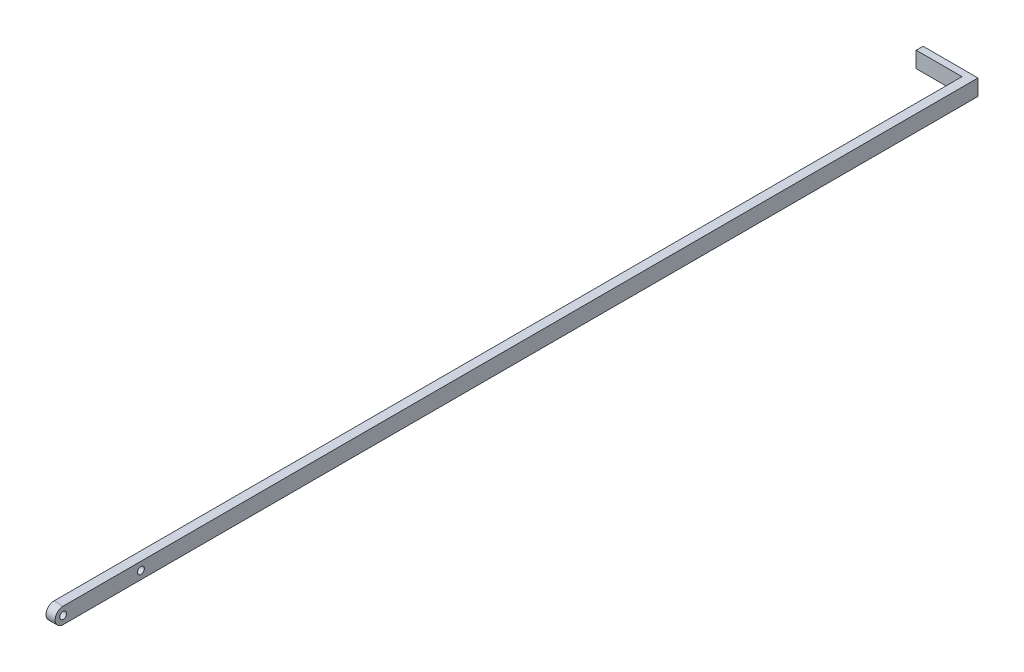
SolidWorks part; units mm, degrees
ref_plane "前视基准面" through (0, 0, 0) normal (0, 0, 1) x (1, 0, 0)
ref_plane "上视基准面" through (0, 0, 0) normal (0, 1, 0) x (1, 0, 0)
ref_plane "右视基准面" through (0, 0, 0) normal (1, 0, 0) x (0, 0, -1)
other "Configuration Table"
sketch "草图1" plane through (0, 0, 0) normal (1, 0, 0) x (0, 0, -1)
  line L0 (400, 7) -> (400, 0)
  line L1 (0, 0) -> (400, 0)
  line L3 (0, 7) -> (400, 7)
  arc A0 (0, 7) -> (0, 0) centre (0, 3.5) ccw
  circle A3 centre (0, 3.5) radius 1.5
  circle A4 centre (34, 3.5) radius 1.5
  dimension "D3" = 34
  dimension "D1" = 400
  dimension "D2" = 7
extrude "凸台-拉伸1" add sketch "草图1" along normal blind 4
sketch "草图2" plane through (0, 0, -400) normal (0, 0, -1) x (-1, 0, 0)
  line L0 (0, 7) -> (20, 7)
  line L1 (20, 7) -> (20, 0)
  line L2 (20, 0) -> (0, 0)
  line L3 (0, 7) -> (0, 0)
  dimension "D1" = 20
extrude "凸台-拉伸2" add sketch "草图2" against normal blind 3
